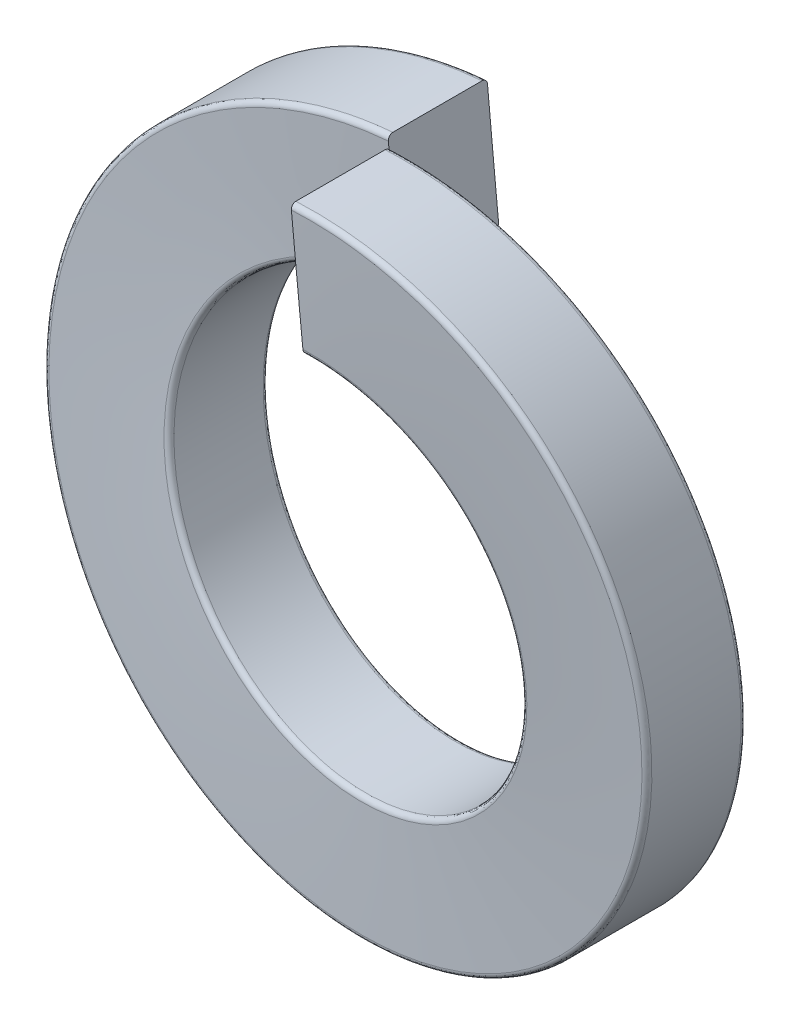
SolidWorks part; units mm, degrees
ref_plane "Front Plane" through (0, 0, 0) normal (0, 0, 1) x (1, 0, 0)
ref_plane "Top Plane" through (0, 0, 0) normal (0, 1, 0) x (1, 0, 0)
ref_plane "Right Plane" through (0, 0, 0) normal (1, 0, 0) x (0, 0, -1)
sketch "Sketch1" plane through (0, 0, 0) normal (0, 0, 1) x (1, 0, 0)
  circle A0 centre (0, 0) radius 13.0048
  circle A1 centre (0, 0) radius 21.0312
  dimension "OD" = 42.0624
  dimension "ID" = 26.0096
sketch "Sketch2" plane through (0, 0, 0) normal (1, 0, 0) x (0, 0, -1)
  line L0 (0, 0) -> (0, 21.0312) construction
  line L1 (0, 21.0312) -> (0, -21.0312) construction
  line L4 (0.635, 21.0312) -> (6.985, 21.0312)
  line L5 (6.985, 21.0312) -> (6.985, 13.0048)
  line L6 (6.985, 13.0048) -> (0.635, 13.0048)
  line L7 (0.635, 13.0048) -> (0.635, 21.0312)
  point P6 (0, 13.0048)
  point P14 (0, -21.0312)
  dimension "Thickness" = 6.35
  dimension "D1" = 0.635
ref_plane "Plane1" through (0, 0, -6.985) normal (0, 0, 1) x (1, 0, 0)
sketch "Sketch3" plane through (0, 0, -6.985) normal (0, 0, 1) x (1, 0, 0)
  circle A0 centre (0, 0) radius 21.0312 construction
  circle A1 centre (0, 0) radius 21.0312
curve "Helix/Spiral1" pitch 6.985 height 6.985 turns 1
sketch "Sketch4" plane through (0, 0, 0) normal (1, 0, 0) x (0, 0, -1)
  line L0 (0.635, 13.0048) -> (0.635, 21.0312) construction
  line L1 (6.985, 13.0048) -> (0.635, 13.0048) construction
  line L2 (6.985, 21.0312) -> (6.985, 13.0048) construction
  line L3 (0.635, 21.0312) -> (6.985, 21.0312) construction
  line L4 (0.635, 13.0048) -> (0.635, 21.0312)
  line L5 (6.985, 13.0048) -> (0.635, 13.0048)
  line L6 (6.985, 21.0312) -> (6.985, 13.0048)
  line L7 (0.635, 21.0312) -> (6.985, 21.0312)
sweep "Sweep1" add profiles "Sketch4" path "Helix/Spiral1"
fillet "Fillet1" radius 0.3175 4 edges
sketch "Sketch5" plane through (0, 0, 0) normal (0, 0, 1) x (1, 0, 0)
  line L2 (0, 0) -> (-0.367, 21.028) construction
  line L3 (0, 21.0312) -> (0.7371, 12.9839)
  line L4 (-0.734, 21.0184) -> (0, 13.0048)
  line L5 (-0.734, 21.0184) -> (0, 0) construction
  line L6 (0, 0) -> (0, 21.0312) construction
  line L7 (0, 13.0048) -> (0, 0)
  line L8 (0, 0) -> (0.7371, 0)
  line L9 (0.7371, 0) -> (0.7371, 12.9839)
  circle A0 centre (0, 0) radius 21.0312 construction
  arc A1 (-0.734, 21.0184) -> (0, 21.0312) centre (0, 0) cw
  circle A2 centre (0, 0) radius 13.0048 construction
  dimension "D1" = 2
extrude "Cut-Extrude1" cut sketch "Sketch5" against normal through all both and the other way through all
ref_plane "Contact Plane1" through (0, 0, 6.3485) normal (0, 0, 1) x (1, 0, 0)
ref_plane "Contact Plane2" through (0, 0, -6.9826) normal (0, 0, 1) x (1, 0, 0)
equation "\"D1@Sketch2\" = \"Thickness@Sketch2\" * 0.1"
equation "\"D4@Helix/Spiral1\" = \"Thickness@Sketch2\" + \"D1@Sketch2\""
equation "\"D1@Fillet1\"=\"D1@Sketch2\"*0.5"
